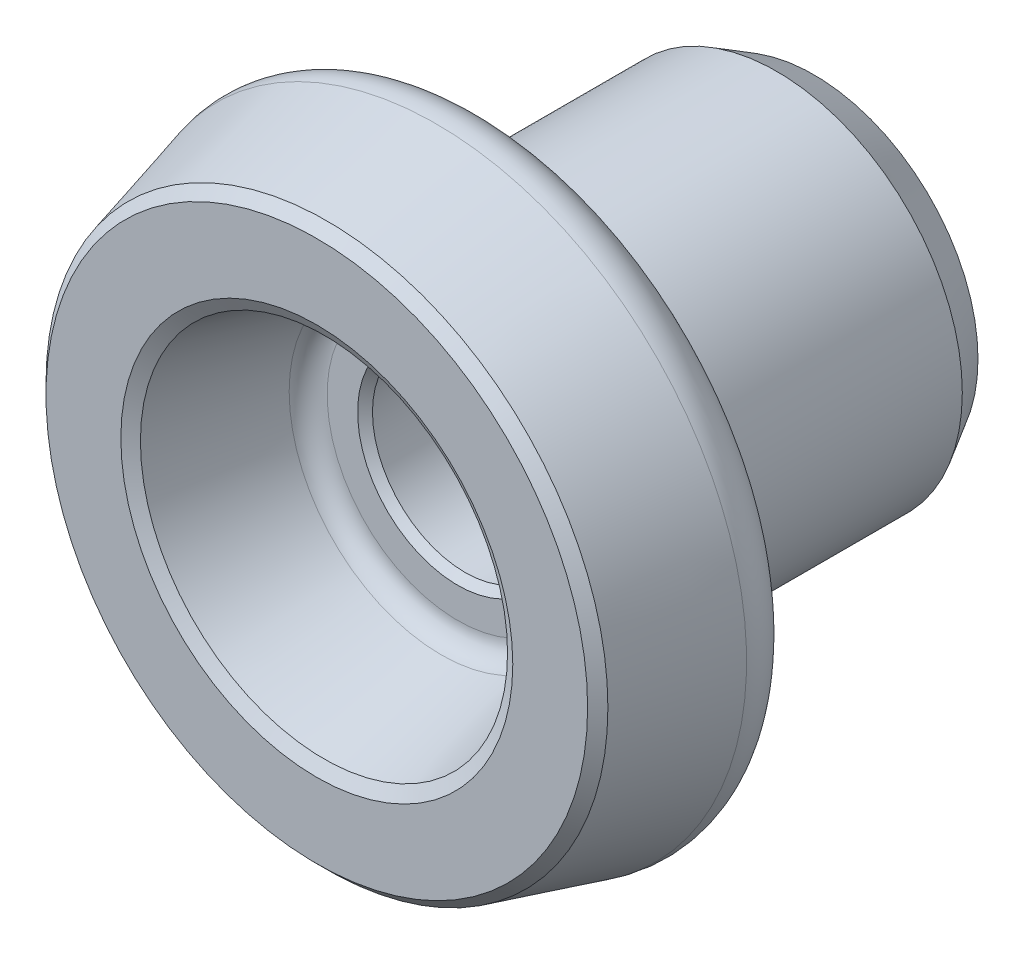
SolidWorks part; units mm, degrees
material "4140 H/T"
ref_plane "Front Plane" through (0, 0, 0) normal (0, 0, 1) x (1, 0, 0)
ref_plane "Top Plane" through (0, 0, 0) normal (0, 1, 0) x (1, 0, 0)
ref_plane "Right Plane" through (0, 0, 0) normal (1, 0, 0) x (0, 0, -1)
sketch "Sketch1" plane through (0, 0, 0) normal (1, 0, 0) x (0, 0, -1)
  line L0 (0, 12.5) -> (0, 18.75)
  line L1 (0, 23.0967) -> (0, -23.0967) construction
  line L2 (0, 18.75) -> (8.0553, 20.9084)
  line L3 (11.2396, 19.0699) -> (13, 12.5)
  line L4 (13, 12.5) -> (31, 12.5)
  line L5 (33.5, 11.0566) -> (33.5, 6.25)
  line L6 (33.5, 6.25) -> (9.5, 6.25)
  line L7 (9.5, 6.25) -> (9.5, 9.9545)
  line L8 (9.5, 9.9545) -> (0, 12.5)
  line L9 (0, 0) -> (-8.2519, 0) construction
  line L10 (18.425, 0) -> (-18.425, 0) construction
  line L12 (31, 12.5) -> (33.5, 11.0566)
  arc A0 (11.2396, 19.0699) -> (8.0553, 20.9084) centre (8.7282, 18.397) ccw
  dimension "D13" = 2.6
  dimension "D14" = 41.994
  dimension "D1" = 12.5
  dimension "D2" = 25
  dimension "D3" = 15
  dimension "D4" = 25
  dimension "D5" = 37.5
  dimension "D6" = 9.5
  dimension "D7" = 75
  dimension "D8" = 15
  dimension "D9" = 33.5
  dimension "D10" = 2.5
  dimension "D11" = 30
  dimension "D12" = 20.5
revolve "Revolve1" add sketch "Sketch1" angle 360 about L9
chamfer "Chamfer2" distance 1 angle 45 1 edges at (-6.25, 0, -33.5)
chamfer "Chamfer3" distance 0.5 angle 45 3 edges at (-18.75, 0, 0) (-12.5, 0, 0) (-6.25, 0, -9.5)
fillet "Fillet2" radius 1.5 1 edges at (-9.9545, 0, -9.5)
fillet "Fillet3" radius 2.5 1 edges at (-12.5, 0, -13)
